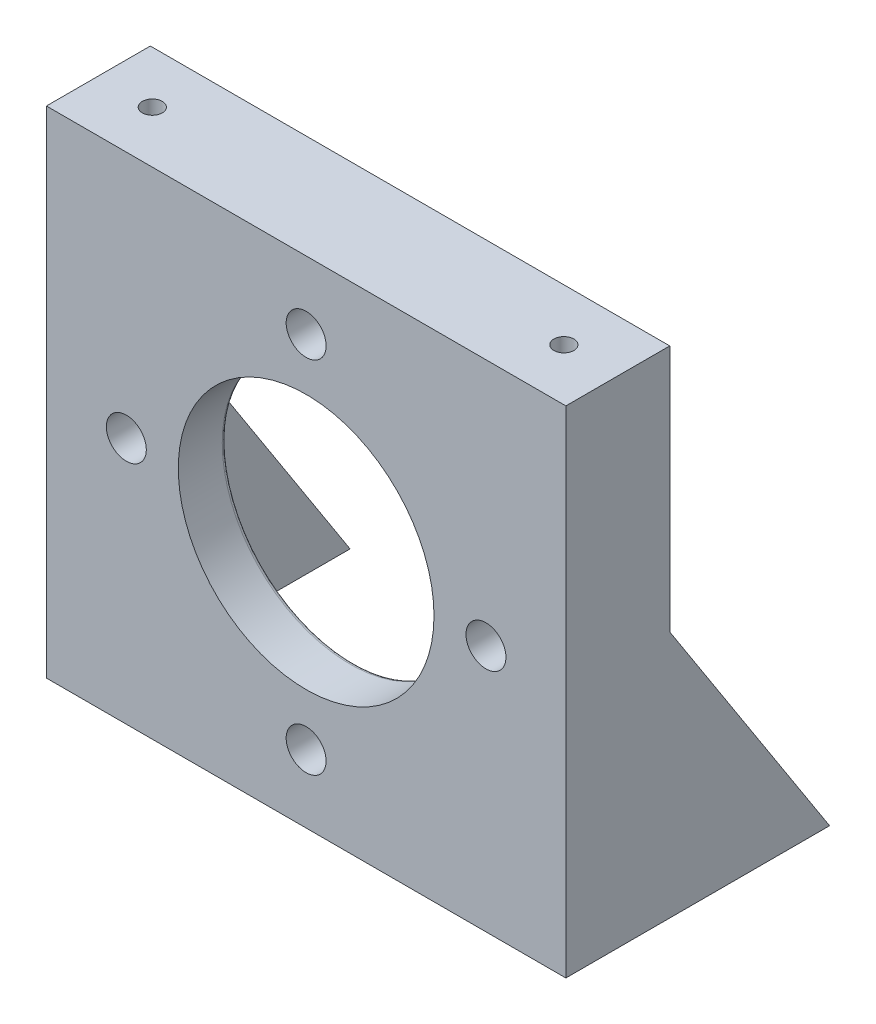
SolidWorks part; units mm, degrees
ref_plane "Front Plane" through (0, 0, 0) normal (0, 0, 1) x (1, 0, 0)
ref_plane "Top Plane" through (0, 0, 0) normal (0, 1, 0) x (1, 0, 0)
ref_plane "Right Plane" through (0, 0, 0) normal (1, 0, 0) x (0, 0, -1)
sketch "Sketch1" plane through (0, 0, 0) normal (0, 0, 1) x (1, 0, 0)
  line L5 (-32.5, -31) -> (32.5, -31)
  line L6 (-32.5, -31) -> (-32.5, 31)
  line L7 (-32.5, 31) -> (32.5, 31)
  line L8 (32.5, -31) -> (32.5, 31)
  line L9 (-32.5, -31) -> (32.5, 31) construction
  line L10 (-32.5, 31) -> (32.5, -31) construction
  point P0 (0, 0)
  dimension "D1" = 62
  dimension "D2" = 65
extrude "Boss-Extrude1" add sketch "Sketch1" against normal blind 13
sketch "Sketch2" plane through (0, 0, 0) normal (1, 0, 0) x (0, 0, -1)
  line L0 (13, 0) -> (33, -31)
  line L1 (13, -31) -> (13, 31) construction
  line L2 (33, -31) -> (13, -31)
  line L3 (13, -31) -> (13, 0)
  line L4 (0, 0) -> (13, 0) construction
  dimension "D1" = 33
extrude "Boss-Extrude2" add sketch "Sketch2" along normal up to surface and the other way up to surface up to face at (32.5, 0, -6.5) other way up to face at (-32.5, 0, -6.5)
sketch "Sketch3" plane through (0, 0, 0) normal (0, 1, 0) x (1, 0, 0)
  line L0 (0, 23) -> (0, 0) construction
  line L1 (27.5, 13) -> (-27.5, 13)
  line L2 (27.5, 13) -> (27.5, 33)
  line L3 (27.5, 33) -> (-27.5, 33)
  line L4 (-27.5, 13) -> (-27.5, 33)
  line L5 (27.5, 13) -> (-27.5, 33) construction
  line L6 (27.5, 33) -> (-27.5, 13) construction
  line L7 (32.5, 13) -> (-32.5, 13) construction
  line L8 (32.5, 33) -> (-32.5, 33) construction
  line L9 (32.5, 33) -> (32.5, 13) construction
  point P0 (0, 23)
  dimension "D1" = 5
extrude "Cut-Extrude1" cut sketch "Sketch3" against normal through all
sketch "Sketch5" plane through (0, 0, 0) normal (0, 0, 1) x (1, 0, 0)
  circle A0 centre (0, 0) radius 16
  dimension "D1" = 32
extrude "Cut-Extrude3" cut sketch "Sketch5" against normal through all
sketch "Sketch4" plane through (0, 0, -13) normal (0, 0, -1) x (-1, 0, 0)
  circle A0 centre (0, 0) radius 26
  dimension "D1" = 52
extrude "Cut-Extrude2" cut sketch "Sketch4" against normal blind 7
sketch "Sketch6" plane through (0, 0, 0) normal (0, 0, 1) x (1, 0, 0)
  line L0 (0, 0) -> (0, 20) construction
  line L1 (0, 20) -> (0, 22.5) construction
  line L2 (0, 22.5) -> (0, 25) construction
  line L3 (0, 25) -> (0, 31) construction
  line L4 (32.5, 31) -> (-32.5, 31) construction
  line L5 (0, 0) -> (20, 0) construction
  line L6 (20, 0) -> (22.5, 0) construction
  line L7 (22.5, 0) -> (25, 0) construction
  line L8 (25, 0) -> (31, 0) construction
  line L9 (0, 0) -> (0, -20) construction
  line L10 (0, -20) -> (0, -22.5) construction
  line L11 (0, -22.5) -> (0, -25) construction
  line L12 (0, -25) -> (0, -31) construction
  line L13 (0, 0) -> (-20, 0) construction
  line L14 (-20, 0) -> (-22.5, 0) construction
  line L15 (-22.5, 0) -> (-25, 0) construction
  line L16 (-25, 0) -> (-31, 0) construction
  circle A0 centre (0, 22.5) radius 2.5
  circle A1 centre (22.5, 0) radius 2.5
  circle A2 centre (0, -22.5) radius 2.5
  circle A3 centre (-22.5, 0) radius 2.5
  point P28 (0, 0)
  dimension "D1" = 5
  dimension "D2" = 6
  dimension "D3" = 4
extrude "Cut-Extrude4" cut sketch "Sketch6" against normal through all
fillet "Fillet1" radius 0.5 3 edges at (-16, 0, -6) (-26, 0, -6) (-26, 0, -13)
sketch "Sketch7" plane through (0, -31, 0) normal (0, -1, 0) x (1, 0, 0)
  line L0 (0, -21.749) -> (0, 2.6257) construction
  line L1 (27, -6.5) -> (27, -13) construction
  line L2 (27, -6.5) -> (27, 0) construction
  line L3 (-32.5, 0) -> (32.5, 0) construction
  line L4 (-27, -6.5) -> (-27, 0) construction
  line L6 (-27.5, -13) -> (27.5, -13) construction
  line L7 (30, -21.65) -> (30, -33) construction
  line L8 (32.5, -33) -> (27.5, -33) construction
  circle A0 centre (27, -6.5) radius 2.5
  circle A1 centre (30, -21.65) radius 1.5
  circle A2 centre (-30, -21.65) radius 1.5
  circle A3 centre (-27, -6.5) radius 2.5
  dimension "D1" = 5
  dimension "D2" = 3
  dimension "D3" = 27
  dimension "D4" = 11.35
sketch "Sketch8" plane through (0, 31, 0) normal (0, 1, 0) x (1, 0, 0)
  line L0 (0, 13) -> (0, 0) construction
  line L1 (32.5, 13) -> (-32.5, 13) construction
  line L2 (-32.5, 13) -> (-32.5, 0) construction
  line L3 (-25.75, 6.5) -> (0, 6.5) construction
  circle A0 centre (-25.75, 6.5) radius 1.5
  circle A2 centre (25.75, 6.5) radius 1.5
  dimension "D1" = 3
  dimension "D2" = 6.75
hole_wizard "Tap Drill for M5x0.8 Tap1" positions "Sketch9" profile "Sketch10" hole size "M5x0.8" standard "ANSI Metric"
sketch "Sketch9" plane through (0, -31, 0) normal (0, -1, 0) x (-1, 0, 0)
  point P0 (27, 6.5)
  point P3 (-27, 6.5)
sketch "Sketch10" plane through (-27, -31, -6.5) normal (1, 0, 0) x (0, 0, -1)
  line L0 (0, 0) -> (0, 16.2618)
  line L1 (0, 16.2618) -> (2.1, 15)
  line L2 (2.1, 15) -> (2.1, 0)
  line L5 (2.1, 0) -> (0, 0)
  line L10 (0, 16.2618) -> (-2.1, 15) construction
  line L11 (0, -6.35) -> (0, 107.95) construction
  dimension "Hole Dia." = 4.2
  dimension "Hole Depth" = 15
  dimension "Drill Angle" = 118
hole_wizard "Tap Drill for M3x0.5 Tap1" positions "Sketch11" profile "Sketch12" hole size "M3x0.5" standard "ANSI Metric"
sketch "Sketch11" plane through (0, -31, 0) normal (0, -1, 0) x (-1, 0, 0)
  point P0 (30, 21.65)
  point P3 (-30, 21.65)
sketch "Sketch12" plane through (-30, -31, -21.65) normal (1, 0, 0) x (0, 0, -1)
  line L0 (0, 0) -> (0, 10.7511)
  line L1 (0, 10.7511) -> (1.25, 10)
  line L2 (1.25, 10) -> (1.25, 0)
  line L5 (1.25, 0) -> (0, 0)
  line L10 (0, 10.7511) -> (-1.25, 10) construction
  line L11 (0, -6.35) -> (0, 107.95) construction
  dimension "Hole Dia." = 2.5
  dimension "Hole Depth" = 10
  dimension "Drill Angle" = 118
hole_wizard "Tap Drill for M3x0.5 Tap2" positions "Sketch13" profile "Sketch14" hole size "M3x0.5" standard "ANSI Metric"
sketch "Sketch13" plane through (0, 31, 0) normal (0, 1, 0) x (1, 0, 0)
  point P0 (25.75, 6.5)
  point P3 (-25.75, 6.5)
sketch "Sketch14" plane through (25.75, 31, -6.5) normal (1, 0, 0) x (0, 0, 1)
  line L0 (0, 0) -> (0, 10.7511)
  line L1 (0, 10.7511) -> (1.25, 10)
  line L2 (1.25, 10) -> (1.25, 0)
  line L5 (1.25, 0) -> (0, 0)
  line L10 (0, 10.7511) -> (-1.25, 10) construction
  line L11 (0, -6.35) -> (0, 107.95) construction
  dimension "Hole Dia." = 2.5
  dimension "Hole Depth" = 10
  dimension "Drill Angle" = 118
